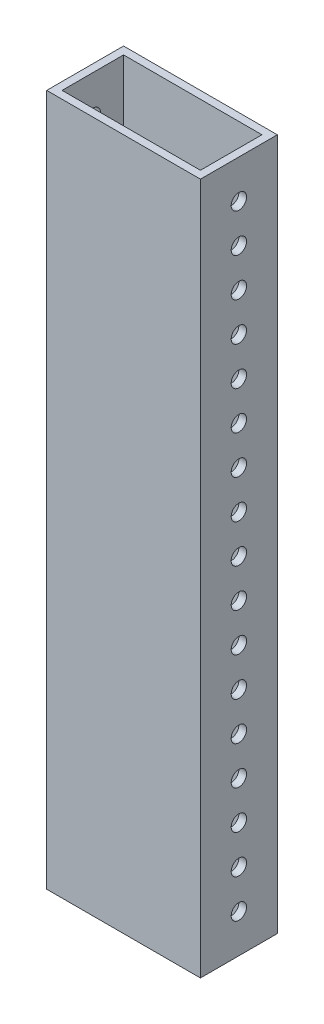
SolidWorks part; units mm, degrees
ref_plane "Front Plane" through (0, 0, 0) normal (0, 0, 1) x (1, 0, 0)
ref_plane "Top Plane" through (0, 0, 0) normal (0, 1, 0) x (1, 0, 0)
ref_plane "Right Plane" through (0, 0, 0) normal (1, 0, 0) x (0, 0, -1)
sketch "Sketch1" plane through (0, 0, 0) normal (0, 1, 0) x (1, 0, 0)
  line L1 (-29.429, 20.3638) -> (21.371, 20.3638)
  line L2 (-29.429, 20.3638) -> (-29.429, -5.0362)
  line L3 (-29.429, -5.0362) -> (21.371, -5.0362)
  line L4 (21.371, 20.3638) -> (21.371, -5.0362)
  line L5 (-29.429, 20.3638) -> (21.371, -5.0362) construction
  line L6 (-29.429, -5.0362) -> (21.371, 20.3638) construction
  line L7 (-26.889, 17.8238) -> (18.831, 17.8238)
  line L8 (-26.889, 17.8238) -> (-26.889, -2.4962)
  line L9 (-26.889, -2.4962) -> (18.831, -2.4962)
  line L10 (18.831, 17.8238) -> (18.831, -2.4962)
  line L11 (-26.889, 17.8238) -> (18.831, -2.4962) construction
  line L12 (-26.889, -2.4962) -> (18.831, 17.8238) construction
  point P0 (-4.029, 7.6638)
  point P5 (-4.029, 7.6638)
  dimension "D1" = 25.4
  dimension "D2" = 50.8
  dimension "D3" = 2.54
  dimension "D4" = 2.54
extrude "Boss-Extrude1" add sketch "Sketch1" along normal blind 228.6
sketch "Sketch2" plane through (21.371, 0, 0) normal (1, 0, 0) x (0, 0, -1)
  line L0 (-5.0362, 228.6) -> (20.3638, 228.6) construction
  line L1 (-5.0362, 228.6) -> (-5.0362, 0) construction
  circle A0 centre (7.6638, 215.9) radius 2.54
  circle A1 centre (7.6638, 203.2) radius 2.54
  circle A2 centre (7.6638, 190.5) radius 2.54
  circle A3 centre (7.6638, 177.8) radius 2.54
  circle A4 centre (7.6638, 165.1) radius 2.54
  circle A5 centre (7.6638, 152.4) radius 2.54
  circle A6 centre (7.6638, 139.7) radius 2.54
  circle A7 centre (7.6638, 127) radius 2.54
  circle A8 centre (7.6638, 114.3) radius 2.54
  circle A9 centre (7.6638, 101.6) radius 2.54
  circle A10 centre (7.6638, 88.9) radius 2.54
  circle A11 centre (7.6638, 76.2) radius 2.54
  circle A12 centre (7.6638, 63.5) radius 2.54
  circle A13 centre (7.6638, 50.8) radius 2.54
  circle A14 centre (7.6638, 38.1) radius 2.54
  circle A15 centre (7.6638, 25.4) radius 2.54
  circle A16 centre (7.6638, 12.7) radius 2.54
  dimension "D1" = 5.08
  dimension "D2" = 12.7
  dimension "D3" = 12.7
  dimension "D4" = 17
extrude "Cut-Extrude1" cut sketch "Sketch2" against normal blind 228.6
